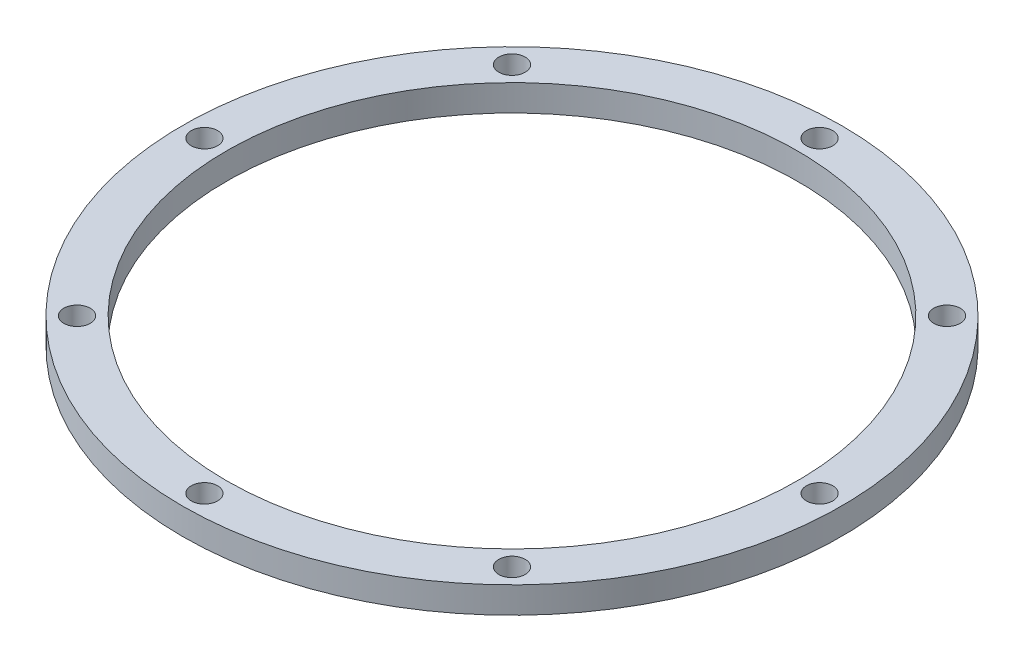
SolidWorks part; units mm, degrees
ref_plane "Спереди" through (0, 0, 0) normal (0, 0, 1) x (1, 0, 0)
ref_plane "Сверху" through (0, 0, 0) normal (0, 1, 0) x (1, 0, 0)
ref_plane "Справа" through (0, 0, 0) normal (1, 0, 0) x (0, 0, -1)
sketch "Эскиз1" plane through (0, 0, 0) normal (0, 1, 0) x (1, 0, 0)
  circle A0 centre (0, 0) radius 75
  point P3 (0, 0)
extrude "Бобышка-Вытянуть1" add sketch "Эскиз1" along normal blind 6 contours A0
sketch "Эскиз2" plane through (0, 6, 0) normal (0, 1, 0) x (1, 0, 0)
  line L0 (0, -75) -> (0, -70) construction
  line L1 (-75, 0) -> (75, 0) construction
  line L2 (0, 75) -> (0, -75) construction
  line L3 (0, 0) -> (-53.033, 53.033) construction
  line L4 (0, 0) -> (53.033, -53.033) construction
  line L5 (0, 0) -> (53.033, 53.033) construction
  line L6 (0, 0) -> (-53.033, -53.033) construction
  circle A0 centre (0, 0) radius 75 construction
  circle A1 centre (-70, 0) radius 3
  circle A2 centre (70, 0) radius 3
  circle A3 centre (0, -70) radius 3
  circle A4 centre (0, 70) radius 3
  circle A5 centre (-49.4975, -49.4975) radius 3
  circle A6 centre (-49.4975, 49.4975) radius 3
  circle A7 centre (49.4975, -49.4975) radius 3
  circle A8 centre (49.4975, 49.4975) radius 3
  point P23 (0, 0)
  dimension "D2" = 5
  dimension "D3" = 5
  dimension "D1" = 5
extrude "Вырез-Вытянуть1" cut sketch "Эскиз2" against normal blind 6
sketch "Эскиз3" plane through (0, 6, 0) normal (0, 1, 0) x (1, 0, 0)
  circle A0 centre (0, 0) radius 65
extrude "Вырез-Вытянуть2" cut sketch "Эскиз3" against normal blind 6
